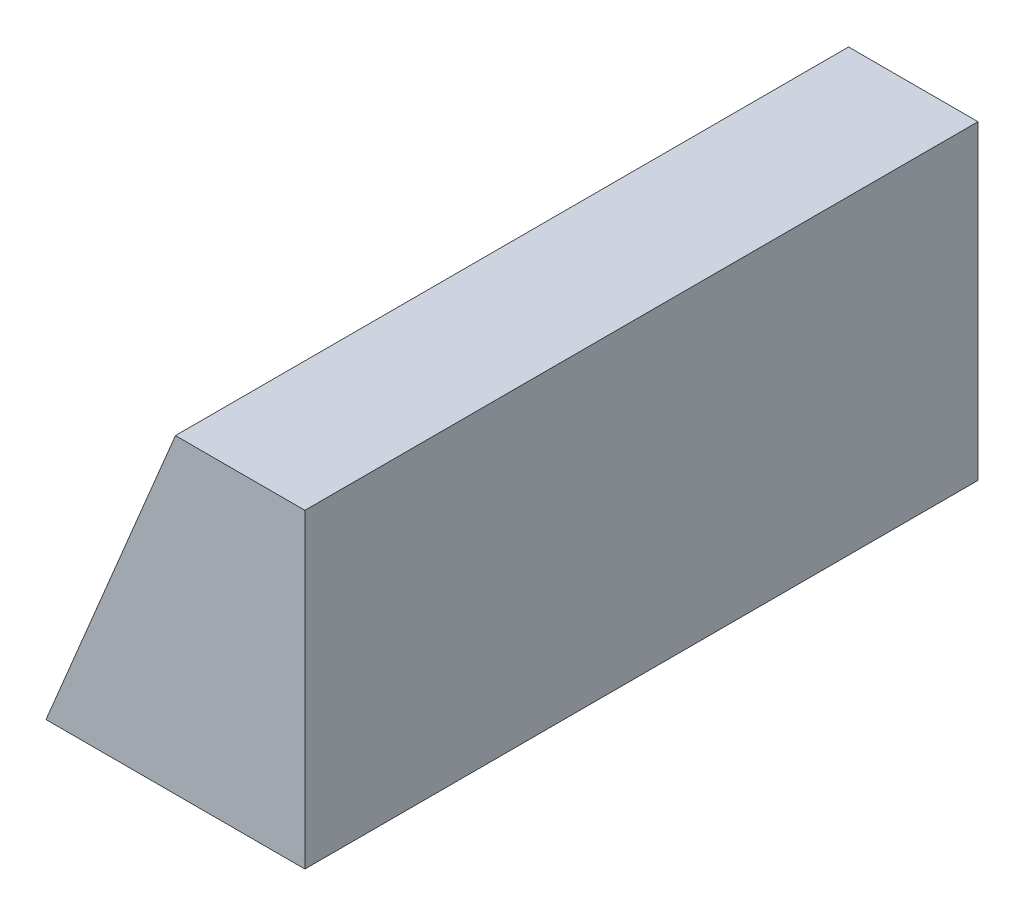
SolidWorks part; units mm, degrees
ref_plane "Front Plane" through (0, 0, 0) normal (0, 0, 1) x (1, 0, 0)
ref_plane "Top Plane" through (0, 0, 0) normal (0, 1, 0) x (1, 0, 0)
ref_plane "Right Plane" through (0, 0, 0) normal (1, 0, 0) x (0, 0, -1)
sketch "Sketch1" plane through (0, 0, 0) normal (0, 0, 1) x (1, 0, 0)
  line L0 (-4.071, -1.9295) -> (5.929, -1.9295)
  line L1 (5.929, -1.9295) -> (5.929, 10.0705)
  line L2 (5.929, 10.0705) -> (0.929, 10.0705)
  line L3 (-4.071, -1.9295) -> (0.929, 10.0705)
  dimension "D1" = 10
  dimension "D2" = 5
  dimension "D3" = 12
extrude "Boss-Extrude1" add sketch "Sketch1" along normal blind 26
